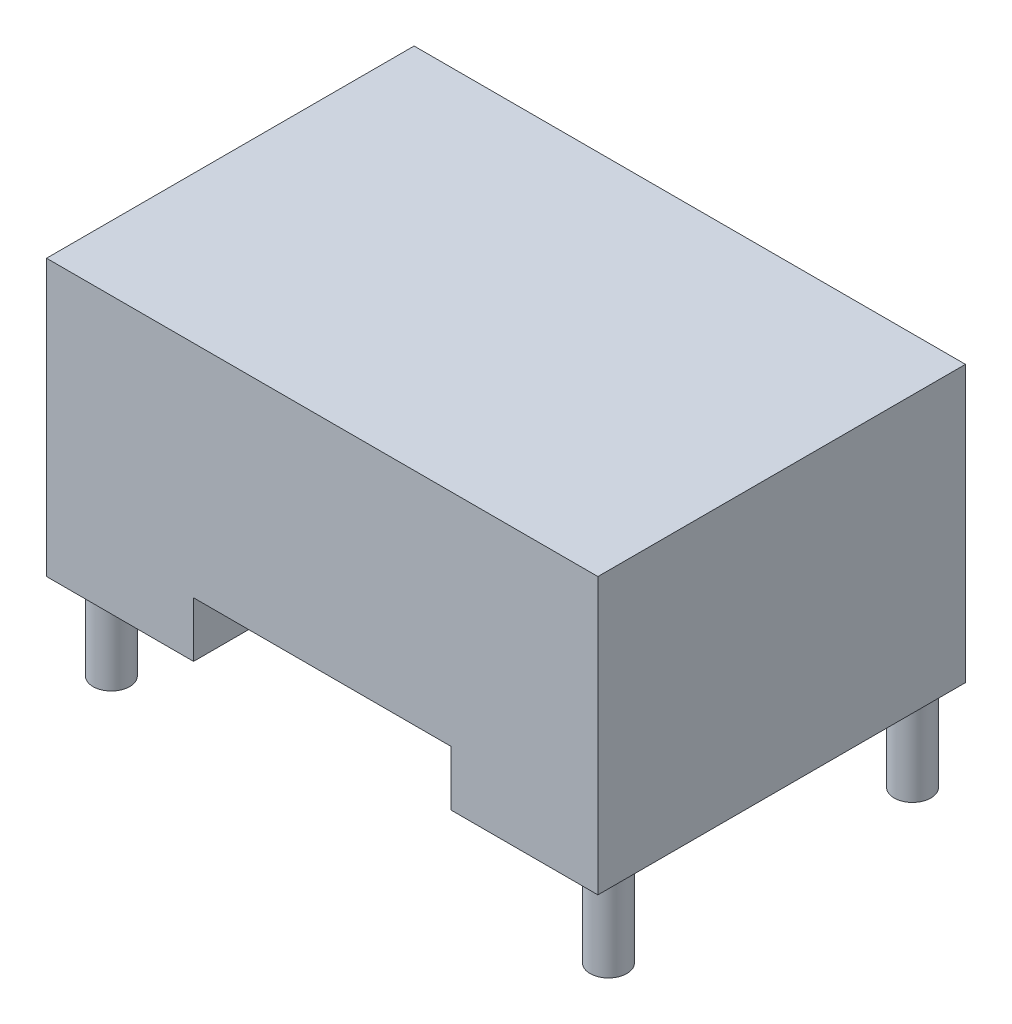
SolidWorks part; units mm, degrees
material "AISI 1015 Steel, Cold Drawn (SS)"
ref_plane "Front Plane" through (0, 0, 0) normal (0, 0, 1) x (1, 0, 0)
ref_plane "Top Plane" through (0, 0, 0) normal (0, 1, 0) x (1, 0, 0)
ref_plane "Right Plane" through (0, 0, 0) normal (1, 0, 0) x (0, 0, -1)
sketch "Sketch1" plane through (0, 0, 0) normal (0, 1, 0) x (1, 0, 0)
  line L0 (-1000, 0) -> (49000, 0) construction
  line L1 (0, -1000) -> (0, 49000) construction
  line L7 (-1500, 1000) -> (1500, 1000)
  line L8 (-1500, 1000) -> (-1500, -1000)
  line L9 (-1500, -1000) -> (1500, -1000)
  line L10 (1500, 1000) -> (1500, -1000)
  line L11 (0, -1000) -> (0, 1000) construction
  line L12 (-1500, 0) -> (1500, 0) construction
  point P4 (0, 0)
  dimension "D1" = 3000
  dimension "D2" = 2000
extrude "Boss-Extrude1" add sketch "Sketch1" along normal blind 1500
sketch "Sketch2" plane through (0, 0, 0) normal (0, 1, 0) x (1, 0, 0)
  line L1 (-700, 1200) -> (700, 1200)
  line L2 (-700, 1200) -> (-700, -1200)
  line L3 (-700, -1200) -> (700, -1200)
  line L4 (700, 1200) -> (700, -1200)
  line L5 (0, -1200) -> (0, 1200) construction
  line L6 (-700, 0) -> (700, 0) construction
  point P0 (0, 0)
  dimension "D1" = 2400
  dimension "D2" = 1400
extrude "Cut-Extrude2" cut sketch "Sketch2" along normal blind 300
sketch "Sketch3" plane through (0, 0, 0) normal (0, 1, 0) x (1, 0, 0)
  circle A0 centre (-1354.7603, 862.1202) radius 100
  circle A1 centre (1349.8339, 862.1202) radius 100
  circle A2 centre (1349.8339, -792.3631) radius 100
  circle A3 centre (-1354.7603, -792.3631) radius 100
  point P8 (1349.8339, 862.1202)
  point P9 (-1354.7603, 862.1202)
  point P10 (0, 0)
  point P11 (1349.8339, -792.3631)
  dimension "D1" = 200
  dimension "D2" = 200
  dimension "D3" = 200
  dimension "D4" = 200
extrude "Boss-Extrude2" add sketch "Sketch3" against normal blind 500
